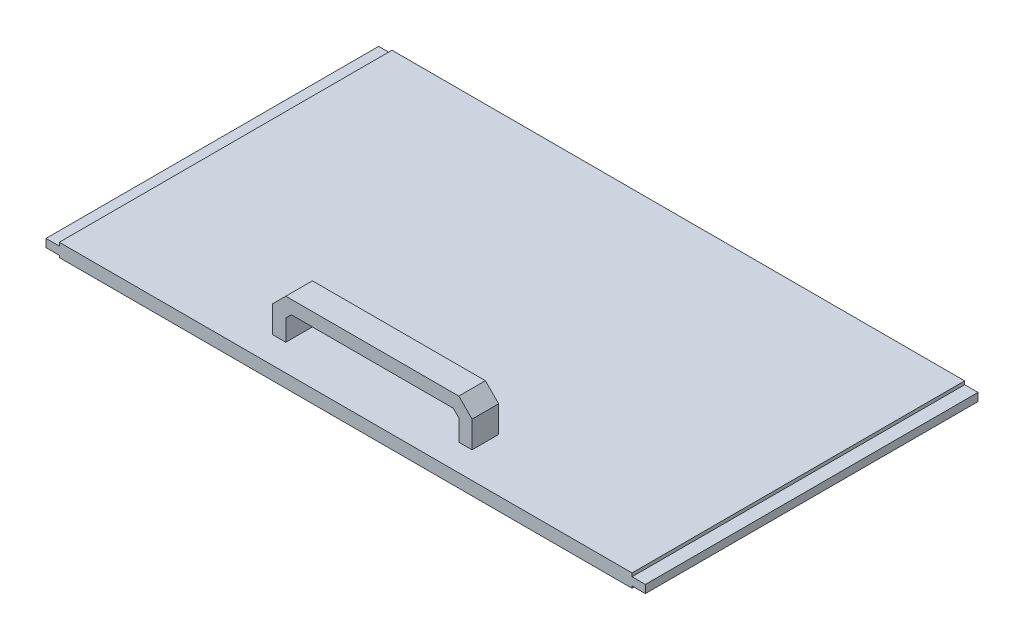
SolidWorks part; units mm, degrees
ref_plane "前视基准面" through (0, 0, 0) normal (0, 0, 1) x (1, 0, 0)
ref_plane "上视基准面" through (0, 0, 0) normal (0, 1, 0) x (1, 0, 0)
ref_plane "右视基准面" through (0, 0, 0) normal (1, 0, 0) x (0, 0, -1)
sketch "草图1" plane through (0, 0, 0) normal (0, 1, 0) x (1, 0, 0)
  line L0 (-192.8964, 123.815) -> (-192.8964, -126.185)
  line L1 (-192.8964, -126.185) -> (237.5336, -126.185)
  line L2 (237.5336, -126.185) -> (237.5336, 123.815)
  line L3 (237.5336, 123.815) -> (-192.8964, 123.815)
  dimension "D1" = 430.43
  dimension "D2" = 250
extrude "凸台-拉伸1" add sketch "草图1" along normal blind 10
sketch "草图2" plane through (237.5336, 0, 0) normal (1, 0, 0) x (0, 0, -1)
  line L0 (123.815, 10) -> (123.815, 7.5) construction
  line L1 (123.815, 10) -> (123.815, 0) construction
  line L2 (123.815, 7.5) -> (-126.185, 7.5) construction
  line L3 (-126.185, 10) -> (-126.185, 0) construction
  line L4 (-126.185, 7.5) -> (-126.185, 10) construction
  line L5 (-126.185, 10) -> (123.815, 10) construction
  line L6 (-126.185, 7.5) -> (-126.185, 1.5)
  line L7 (-126.185, 1.5) -> (123.815, 1.5)
  line L8 (123.815, 1.5) -> (123.815, 7.5)
  line L9 (123.815, 7.5) -> (-126.185, 7.5)
  dimension "D1" = 2.5
  dimension "D2" = 6
extrude "凸台-拉伸2" add sketch "草图2" along normal blind 10
ref_plane "基准面1" through (22.3186, 0, 0) normal (1, 0, 0) x (0, 0, -1)
mirror "镜向1" about plane through (22.3186, 0, 0) normal (1, 0, 0) of "凸台-拉伸2"
sketch "草图3" plane through (0, 10, 0) normal (0, 1, 0) x (1, 0, 0)
  line L0 (-52.6814, -106.185) -> (97.3186, -106.185)
  line L1 (97.3186, -106.185) -> (97.3186, -86.185)
  line L2 (97.3186, -86.185) -> (-52.6814, -86.185)
  line L3 (-52.6814, -86.185) -> (-52.6814, -106.185)
  line L4 (237.5336, 123.815) -> (-192.8964, 123.815)
  line L5 (-192.8964, 123.815) -> (-192.8964, -126.185)
  line L6 (-192.8964, -126.185) -> (237.5336, -126.185)
  line L7 (237.5336, -126.185) -> (237.5336, 123.815)
  line L8 (237.5336, 123.815) -> (-192.8964, 123.815) construction
  line L9 (-192.8964, 123.815) -> (-192.8964, -126.185) construction
  line L10 (-192.8964, -126.185) -> (237.5336, -126.185) construction
  line L11 (237.5336, -126.185) -> (237.5336, 123.815) construction
  point P8 (22.3186, -126.185)
  dimension "D2" = 20
  dimension "D3" = 150
  dimension "D4" = 75
  dimension "D5" = 20
  dimension "D1" = 0
extrude "凸台-拉伸3" add sketch "草图3" along normal blind 30
sketch "草图4" plane through (0, 0, 86.185) normal (0, 0, -1) x (-1, 0, 0)
  line L4 (-97.3186, 10) -> (52.6814, 10)
  line L5 (52.6814, 10) -> (52.6814, 40)
  line L6 (52.6814, 40) -> (-97.3186, 40)
  line L7 (-97.3186, 40) -> (-97.3186, 10)
  line L8 (-97.3186, 10) -> (52.6814, 10) construction
  line L9 (52.6814, 10) -> (52.6814, 40) construction
  line L10 (52.6814, 40) -> (-97.3186, 40) construction
  line L11 (-97.3186, 40) -> (-97.3186, 10) construction
  dimension "D1" = 0
chamfer "倒角2" distance 10 angle 45 1 edges at (97.3186, 40, 96.185)
chamfer "倒角3" distance 10 angle 45 1 edges at (-52.6814, 40, 96.185)
sketch "草图5" plane through (0, 0, 86.185) normal (0, 0, -1) x (-1, 0, 0)
  line L6 (-87.3186, 20) -> (-87.3186, 10)
  line L7 (-87.3186, 10) -> (42.6814, 10)
  line L8 (42.6814, 10) -> (42.6814, 20)
  line L9 (-97.3186, 10) -> (52.6814, 10) construction
  line L12 (42.6814, 20) -> (42.6814, 25.8579)
  line L13 (42.6814, 25.8579) -> (38.5393, 30)
  line L14 (38.5393, 30) -> (-83.1765, 30)
  line L15 (-83.1765, 30) -> (-87.3186, 25.8579)
  line L16 (-87.3186, 25.8579) -> (-87.3186, 20)
  line L17 (-87.3186, 20) -> (42.6814, 20)
  line L18 (42.6814, 20) -> (42.6814, 25.8579)
  line L19 (42.6814, 25.8579) -> (38.5393, 30)
  line L20 (38.5393, 30) -> (-83.1765, 30)
  line L21 (-83.1765, 30) -> (-87.3186, 25.8579)
  line L22 (-87.3186, 25.8579) -> (-87.3186, 20)
  line L23 (-87.3186, 20) -> (42.6814, 20) construction
  point P4 (0, 0)
  dimension "D1" = 10
extrude "切除-拉伸2" cut sketch "草图5" against normal blind 30
